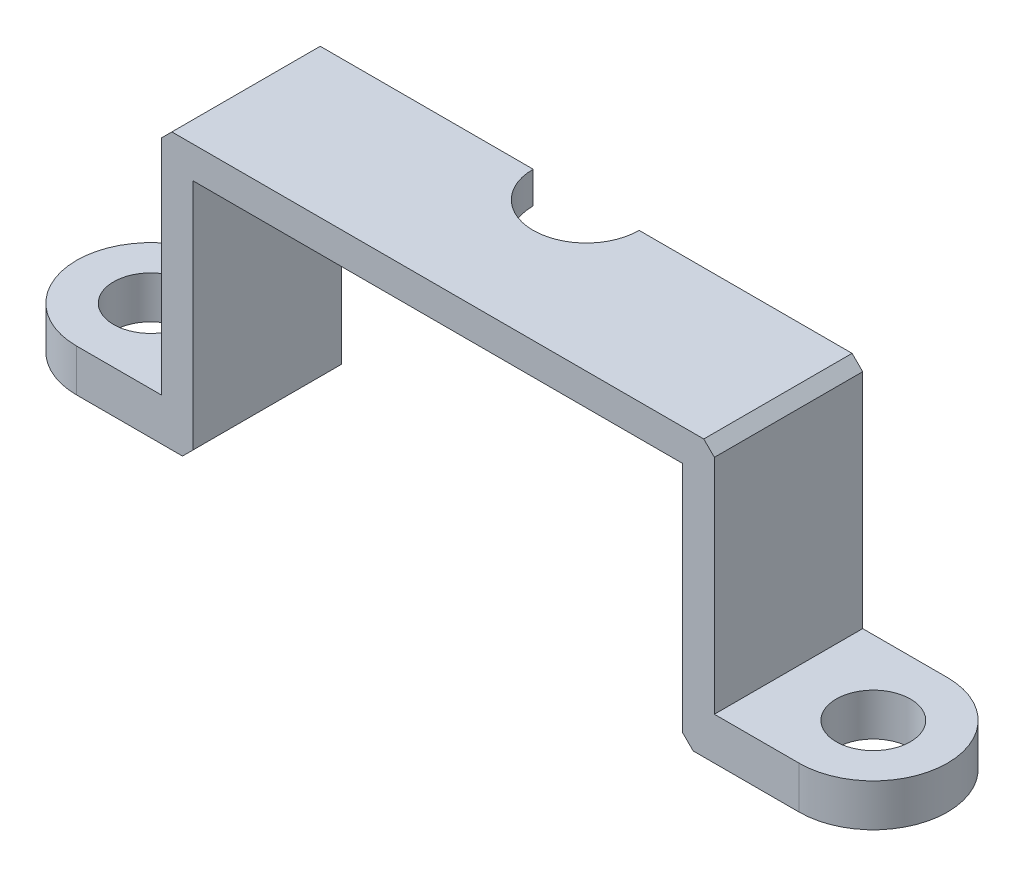
SolidWorks part; units mm, degrees
ref_plane "Front Plane" through (0, 0, 0) normal (0, 0, 1) x (1, 0, 0)
ref_plane "Top Plane" through (0, 0, 0) normal (0, 1, 0) x (1, 0, 0)
ref_plane "Right Plane" through (0, 0, 0) normal (1, 0, 0) x (0, 0, -1)
sketch "Sketch1" plane through (0, 0, 0) normal (0, 0, 1) x (1, 0, 0)
  line L0 (0, 0) -> (11.55, 0) construction
  line L1 (0, 11.5) -> (11.55, 11.5)
  line L2 (11.55, 11.5) -> (11.55, 0)
  line L3 (11.55, 0) -> (21.05, 0)
  line L4 (21.05, 0) -> (21.05, 2)
  line L5 (21.05, 2) -> (13.05, 2)
  line L6 (13.05, 2) -> (13.05, 13)
  line L7 (13.05, 13) -> (0, 13)
  line L8 (0, 13) -> (0, 11.5)
  line L9 (0, 0) -> (0, 11.5) construction
  dimension "D1" = 1.5
  dimension "D2" = 1.5
  dimension "D3" = 2
  dimension "D4" = 11.5
  dimension "D5" = 8
  dimension "D6" = 11.55
extrude "Boss-Extrude1" add sketch "Sketch1" along normal blind 7
sketch "Sketch2" plane through (0, 2, 0) normal (0, 1, 0) x (1, 0, 0)
  line L0 (13.05, -3.5) -> (21.05, -3.5) construction
  line L1 (13.05, -7) -> (13.05, 0) construction
  line L2 (21.05, -7) -> (21.05, 0) construction
  line L3 (21.05, -7) -> (13.05, -7) construction
  line L4 (21.05, 0) -> (13.05, 0) construction
  line L5 (17.05, 0) -> (21.05, 0)
  line L6 (21.05, 0) -> (21.05, -7)
  line L7 (21.05, -7) -> (17.05, -7)
  circle A0 centre (17.05, -3.5) radius 1.75
  arc A1 (17.05, -7) -> (17.05, 0) centre (17.05, -3.5) ccw
  dimension "D1" = 3.5
extrude "Cut-Extrude1" cut sketch "Sketch2" against normal through all
chamfer "Chamfer1" distance 0.5 angle 45 2 edges at (13.05, 13, 3.5) (11.55, 0, 3.5)
mirror "Mirror1" about plane through (0, 0, 0) normal (1, 0, 0) of "Chamfer1", "Cut-Extrude1", "Boss-Extrude1"
sketch "Sketch3" plane through (0, 13, 0) normal (0, 1, 0) x (1, 0, 0)
  line L0 (-2.5, 0) -> (2.5, 0)
  arc A0 (-2.5, 0) -> (2.5, 0) centre (0, 0) ccw
  dimension "D1" = 5
extrude "Cut-Extrude2" cut sketch "Sketch3" against normal through all
